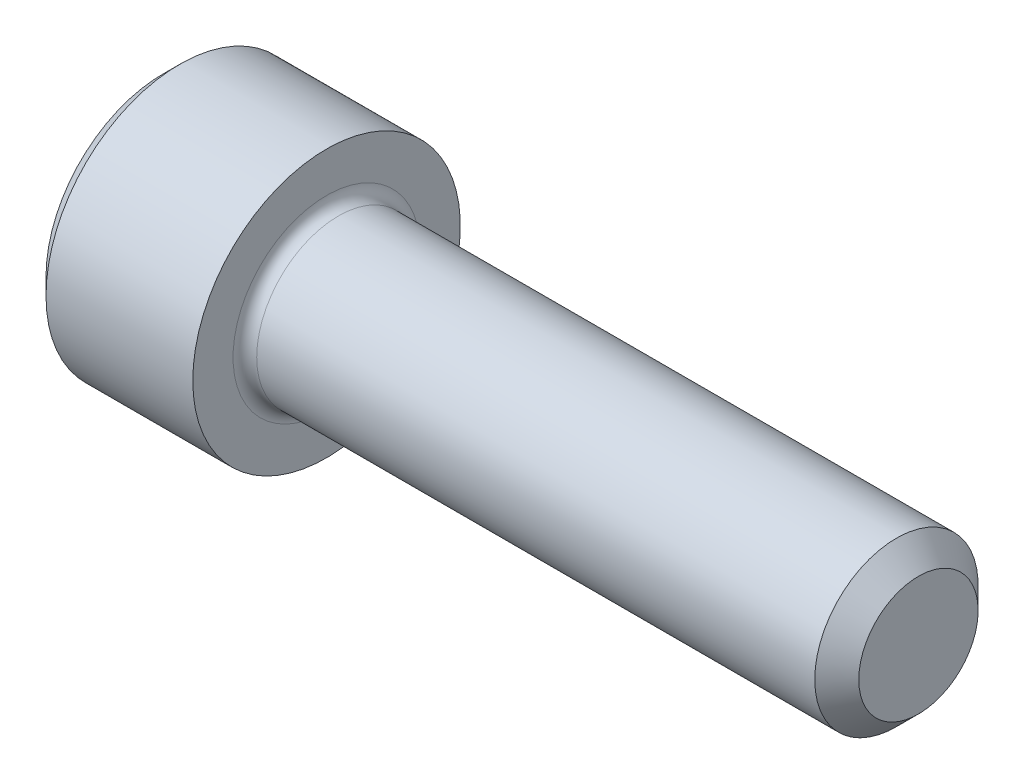
SolidWorks part; units mm, degrees
revolve "Base-Revolve" add sketch "BodySke"
sketch "BodySke" plane through (0, 0, 0) normal (0, 0, 1) x (1, 0, 0)
  line L0 (0, 0) -> (0, 2.5146)
  line L1 (0.3556, 2.8702) -> (3.5052, 2.8702)
  line L2 (3.5052, 2.8702) -> (3.5052, 1.7526)
  line L3 (3.5052, 1.7526) -> (15.7328, 1.7526)
  line L4 (16.2052, 1.2802) -> (16.2052, 0)
  line L5 (16.2052, 0) -> (0, 0)
  line L6 (-31.75, 0) -> (127, 0) construction
  line L7 (0, 2.5146) -> (0.3556, 2.8702)
  line L8 (16.2052, 1.2802) -> (15.7328, 1.7526)
  line L9 (0, -2.5146) -> (0.3556, -2.8702) construction
  line L10 (16.2052, -1.2802) -> (15.7328, -1.7526) construction
  line L11 (4.2977, 9.525) -> (4.2977, 3.175) construction
  line L12 (3.5052, 9.525) -> (3.5052, 3.175) construction
  line L13 (-21.8948, 9.525) -> (-21.8948, 3.175) construction
  dimension "Diameter" = 3.5052
  dimension "Head_ht" = 3.5052
  dimension "Length" = 12.7
  dimension "Body_ch_ang" = 45
  dimension "Head_dia" = 5.7404
  dimension "Head_ch_ang" = 45
  dimension "Head_side_ht" = 3.1496
  dimension "Minor_dia" = 2.5603
  dimension "Advance" = 0.7925
  dimension "Thread_nom" = 12.7
  dimension "Thread_length" = 38.1
cosmetic thread "ThreadCosmetic"
fillet "Fillet1" radius 0.254 1 edges at (3.5052, 0, 1.7526)
other "Defeature"
material "Alloy Steel"
ref_plane "Plane1" through (0, 0, 0) normal (0, 0, 1) x (1, 0, 0)
ref_plane "Plane2" through (0, 0, 0) normal (0, 1, 0) x (1, 0, 0)
ref_plane "Plane3" through (0, 0, 0) normal (1, 0, 0) x (0, 0, -1)
sketch "Sketch2" plane through (0, 0, 0) normal (0, 0, 1) x (1, 0, 0)
  line L0 (0, 1.3843) -> (1.6256, 1.3843)
  line L1 (1.6256, 1.3843) -> (2.4248, 0)
  line L2 (-31.75, 0) -> (127, 0) construction
  line L3 (2.4248, 0) -> (0, 0)
  line L4 (0, 0) -> (0, 1.3843)
  line L5 (0, 2.5146) -> (0, -2.5146) construction
  line L6 (0, 0) -> (47.625, 0) construction
  line L7 (3.5052, -2.8702) -> (3.5052, 2.8702) construction
  dimension "D1" = 1.3843
  dimension "D2" = 60
revolve "Hex-PreBroach" cut sketch "Sketch2" angle 360 about L6
sketch "Sketch3" plane through (0, 0, 0) normal (-1, 0, 0) x (0, 0.5, 0.866)
  line L0 (0.7992, 1.3843) -> (-0.7992, 1.3843)
  line L1 (-0.7992, 1.3843) -> (-1.5985, 0)
  line L2 (0.7992, 1.3843) -> (1.5985, 0)
  line L3 (0.7992, -1.3843) -> (1.5985, 0)
  line L4 (0.7992, -1.3843) -> (-0.7992, -1.3843)
  line L5 (-0.7992, -1.3843) -> (-1.5985, 0)
  dimension "D1" = 1.3843
  dimension "D2" = 1.3843
  dimension "Hex_size" = 2.7686
extrude "Hex" cut sketch "Sketch3" against normal blind 1.6256
sketch "Sketch4" plane through (0, 0, 0) normal (-1, 0, 0) x (0, 0, 1)
  line L0 (0, 0) -> (1.7399, 0)
  line L1 (0, 0) -> (6.1484, 3.5498) construction
  line L2 (0, 0) -> (0.8699, 1.5068)
  line L3 (1.4457, 0.3947) -> (1.6607, 0.5189)
  line L4 (1.0647, 1.0546) -> (1.2797, 1.1788)
  arc A0 (1.4457, 0.3947) -> (1.0647, 1.0546) centre (0, 0) ccw
  arc A1 (1.7399, 0) -> (1.6607, 0.5189) centre (0, 0) ccw
  arc A2 (0.8699, 1.5068) -> (1.2797, 1.1788) centre (0, 0) cw
  dimension "D1" = 30
  dimension "D2" = 60
  dimension "Spline_p_dim" = 0.762
  dimension "D3" = 0.381
extrude "Spline" [suppressed] cut sketch "Sketch4" against normal blind 1.6256
pattern_circular "CirPattern1" [suppressed] count 6 every 60
sketch "Sketch5" plane through (0, 0, 0) normal (0, 0, 1) x (1, 0, 0)
  line L0 (-31.75, 0) -> (127, 0) construction
  line L2 (0, 2.5146) -> (0, -2.5146) construction
  circle A0 centre (1.27, 0) radius 0.4445
  dimension "Drilled_hole_dia" = 0.889
  dimension "Drilled_hole_loc" = 1.27
extrude "Hole" [suppressed] cut sketch "Sketch5" against normal through all and the other way through all
pattern_circular "Drilled-4" [suppressed] count 2 every 60
pattern_circular "Drilled-6" [suppressed] count 3 every 60
sketch "ThdSchSke" plane through (0, 0, 0) normal (0, 0, 1) x (1, 0, 0)
  line L0 (4.2977, -1.2802) -> (3.9669, -1.7526)
  line L1 (4.2977, -1.2802) -> (4.6285, -1.7526)
  line L2 (4.6285, -1.7526) -> (4.6285, -2.1908)
  line L3 (-3.175, 0) -> (5.1513, 0) construction
  line L5 (4.6285, -2.1908) -> (3.9669, -2.1908)
  line L6 (3.9669, -2.1908) -> (3.9669, -1.7526)
  line L7 (0, 2.5146) -> (0, -2.5146) construction
  dimension "Thread_minor" = 2.5603
  dimension "Diameter" = 3.5052
  dimension "Start" = 4.2977
revolve "ThreadSchematic" [suppressed] cut sketch "ThdSchSke" angle 360 about L3
pattern_linear "ThdSchPat" [suppressed]
equation "\"D2@Sketch3\" = \"Hex_size@Sketch3\" / 2"
equation "\"D1@Sketch3\" = \"Hex_size@Sketch3\" / 2"
equation "\"D1@Sketch2\" = \"Hex_size@Sketch3\" / 2"
equation "\"D3@Sketch4\" = \"Spline_p_dim@Sketch4\" / 2"
equation "\"Thread_minor@ThreadCosmetic\"  =  \"Minor_dia@BodySke\""
equation "\"D2@CirPattern1\" = 360 / \"Num_teeth@CirPattern1\""
equation "\"Wall_thickness@Sketch2\" = \"Head_ht@BodySke\" - \"Key_eng@Hex\""
equation "\"Thread_length@ThreadCosmetic\" = ((sgn( (\"Length@BodySke\" - \"Advance@BodySke\" ) - \"Thread_nom@BodySke\" )-1)*( (\"Length@BodySke\" - \"Advance@BodySke\" ) - \"Thread_nom@BodySke\" ))/-2+ \"Thread_nom@BodySke\""
equation "\"Thread_minor@ThdSchSke\" = \"Minor_dia@BodySke\""
equation "\"Diameter@ThdSchSke\" = \"Diameter@BodySke\""
equation "\"Overcut@ThdSchSke\" = \"Diameter@BodySke\" * 1.25"
equation "\"Start@ThdSchSke\" = \"Head_ht@BodySke\" + \"Length@BodySke\" - \"Thread_length@ThreadCosmetic\"  '---Non-countersunk---"
equation "\"Num_threads@ThdSchPat\" = int( \"Thread_length@ThreadCosmetic\" / \"Advance@BodySke\" + 0.999 )  + 1"
equation "\"Advance@ThdSchPat\" = \"Thread_length@ThreadCosmetic\" /  (\"Num_threads@ThdSchPat\" - 1) 'relax it"
equation "\"Num_threads@ThdSchPat\" = \"Num_threads@ThdSchPat\" - sgn( \"Num_threads@ThdSchPat\" - 1) '---chamfered tips only---"
